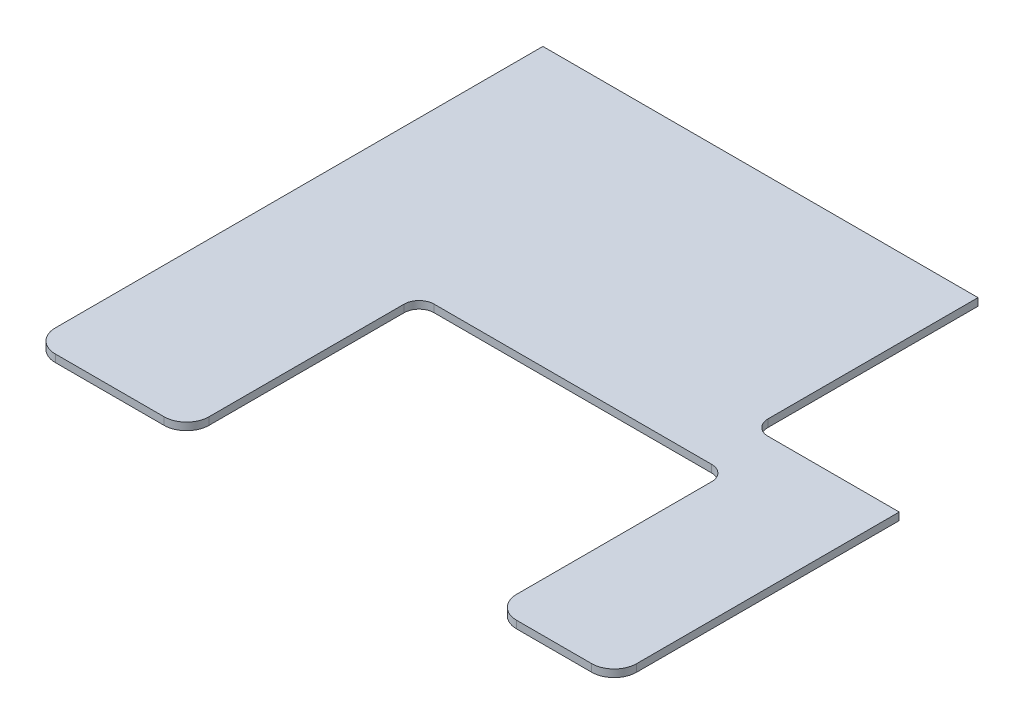
SolidWorks part; units mm, degrees
ref_plane "Plano frontal" through (0, 0, 0) normal (0, 0, 1) x (1, 0, 0)
ref_plane "Plano superior" through (0, 0, 0) normal (0, 1, 0) x (1, 0, 0)
ref_plane "Plano direito" through (0, 0, 0) normal (1, 0, 0) x (0, 0, -1)
sketch "Esboço1" plane through (0, 0, 0) normal (0, 1, 0) x (1, 0, 0)
  line L1 (387.5, -340) -> (-387.5, -340)
  line L2 (387.5, -340) -> (387.5, 340)
  line L3 (387.5, 340) -> (-387.5, 340)
  line L4 (-387.5, -340) -> (-387.5, 340)
  line L5 (387.5, -340) -> (-387.5, 340) construction
  line L6 (387.5, 340) -> (-387.5, -340) construction
  point P0 (0, 0)
  dimension "D1" = 680
  dimension "D2" = 775
extrude "Ressalto-extrusão1" add sketch "Esboço1" along normal blind 10
sketch "Esboço2" plane through (0, 10, 0) normal (0, 1, 0) x (1, 0, 0)
  line L0 (-387.5, -340) -> (387.5, -340) construction
  line L1 (387.5, 340) -> (192.5, 340)
  line L2 (387.5, 340) -> (387.5, 40)
  line L3 (387.5, 40) -> (212.5, 40)
  line L4 (192.5, 340) -> (192.5, 60)
  line L5 (-182.5, -340) -> (227.5, -340)
  line L6 (-182.5, -340) -> (-182.5, -50)
  line L7 (-162.5, -30) -> (207.5, -30)
  line L8 (227.5, -340) -> (227.5, -50)
  line L9 (387.5, -340) -> (387.5, 340) construction
  arc A0 (-182.5, -50) -> (-162.5, -30) centre (-162.5, -50) cw
  arc A1 (207.5, -30) -> (227.5, -50) centre (207.5, -50) cw
  arc A2 (212.5, 40) -> (192.5, 60) centre (212.5, 60) cw
  point P15 (-182.5, -30)
  point P20 (192.5, 40)
  dimension "D6" = 20
  dimension "D1" = 160
  dimension "D2" = 410
  dimension "D3" = 310
  dimension "D4" = 300
  dimension "D5" = 195
extrude "Corte-extrusão1" cut sketch "Esboço2" against normal through all
fillet "Filete1" radius 30 4 edges at (-182.5, 5, 340) (-387.5, 5, 340) (227.5, 5, 340) (387.5, 5, 340)
sketch "Esboço3" plane through (0, 10, 0) normal (0, 1, 0) x (1, 0, 0)
  line L0 (-355.247, -184.6919) -> (-355.247, 762.6414) construction
  line L1 (195.5984, 93.7097) -> (198.7505, 207.5792)
  line L2 (198.7505, 207.5792) -> (260.2164, 207.5792) construction
  line L3 (260.2164, 207.5792) -> (270.0667, 96.8618)
  line L4 (217.0581, 40) -> (217.0581, 64.8635)
  line L5 (212.5, 40) -> (387.5, 40) construction
  line L6 (242.4451, 40) -> (242.4451, 62.7446)
  circle A0 centre (237.9752, 100.6125) radius 24.8821
  arc A1 (195.5984, 93.7097) -> (270.0667, 96.8618) centre (232.68, 98.8905) ccw
  arc A2 (198.7505, 207.5792) -> (260.2164, 207.5792) centre (229.4834, 207.5792) cw
